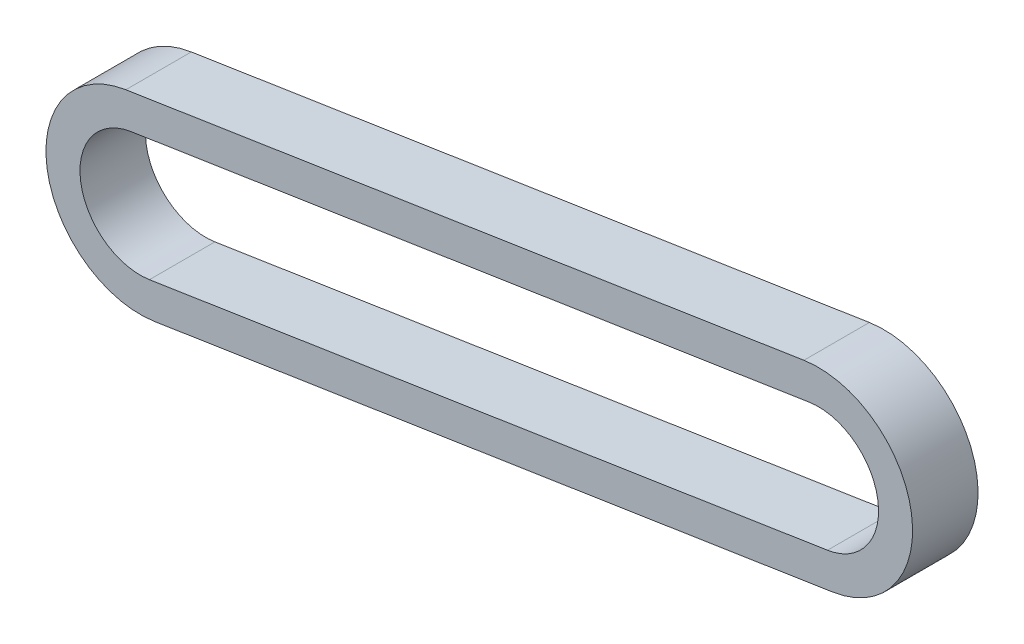
SolidWorks part; units mm, degrees
ref_plane "Front Plane" through (0, 0, 0) normal (0, 0, 1) x (1, 0, 0)
ref_plane "Top Plane" through (0, 0, 0) normal (0, 1, 0) x (1, 0, 0)
ref_plane "Right Plane" through (0, 0, 0) normal (1, 0, 0) x (0, 0, -1)
sketch "Sketch1" plane through (0, 0, 0) normal (0, 0, 1) x (1, 0, 0)
  line L2 (0.446, -2.8868) -> (33.3299, 2.1932)
  line L3 (32.438, 7.9668) -> (-0.446, 2.8868)
  line L6 (32.1859, 9.5984) -> (-0.698, 4.5184)
  line L7 (0.698, -4.5184) -> (33.5819, 0.5616)
  circle A0 centre (0, 0) radius 2.921 construction
  circle A1 centre (32.8839, 5.08) radius 2.921 construction
  arc A4 (33.3299, 2.1932) -> (32.438, 7.9668) centre (32.8839, 5.08) ccw
  arc A5 (-0.446, 2.8868) -> (0.446, -2.8868) centre (0, 0) ccw
  arc A8 (-0.698, 4.5184) -> (0.698, -4.5184) centre (0, 0) ccw
  arc A9 (33.5819, 0.5616) -> (32.1859, 9.5984) centre (32.8839, 5.08) ccw
  dimension "D1" = 5.842
  dimension "D2" = 5.842
  dimension "D5" = 84.9012
  dimension "D6" = 95.2747
  dimension "D3" = 5.08
  dimension "D4" = 33.274
  dimension "D7" = 1.651
extrude "Boss-Extrude1" add sketch "Sketch1" along normal blind 3.175
